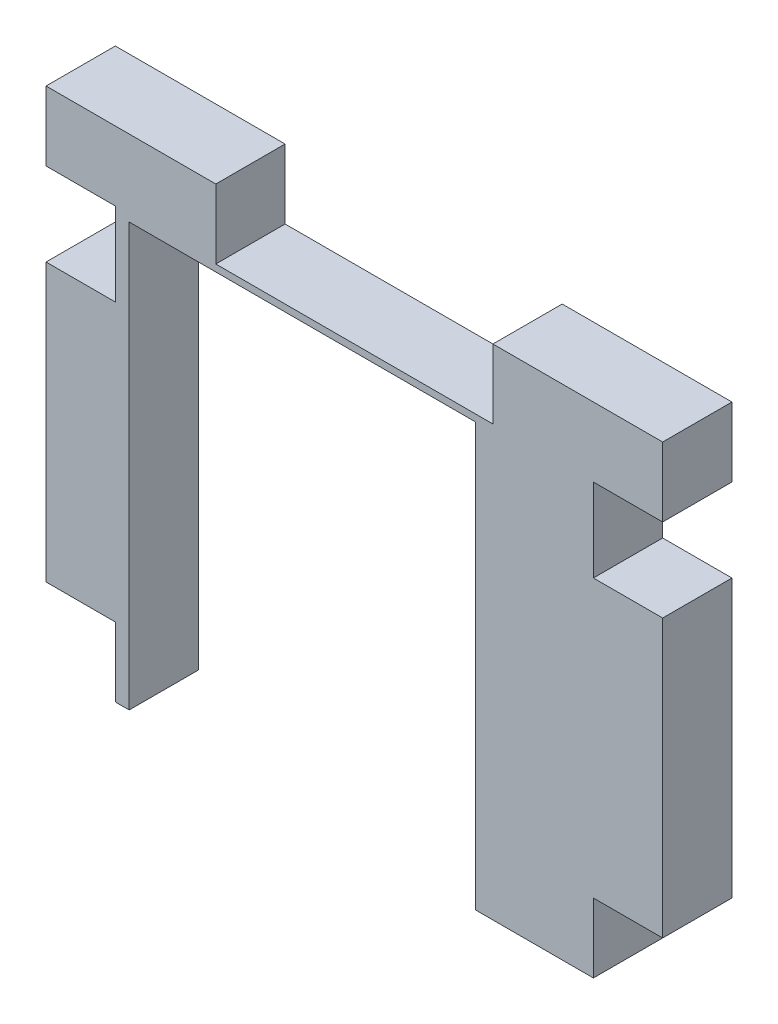
SolidWorks part; units mm, degrees
ref_plane "Front Plane" through (0, 0, 0) normal (0, 0, 1) x (1, 0, 0)
ref_plane "Top Plane" through (0, 0, 0) normal (0, 1, 0) x (1, 0, 0)
ref_plane "Right Plane" through (0, 0, 0) normal (1, 0, 0) x (0, 0, -1)
sketch "Sketch1" plane through (0, 0, 0) normal (0, 0, 1) x (1, 0, 0)
  line L0 (5, 36) -> (44.5, 36)
  line L1 (0, 0) -> (44.5, 0)
  line L2 (0, 0) -> (0, 41)
  line L3 (0, 41) -> (44.5, 41)
  line L4 (44.5, 0) -> (44.5, 41)
  line L5 (12.25, 0) -> (32.25, 0)
  line L6 (12.25, 0) -> (12.25, 5)
  line L7 (12.25, 5) -> (32.25, 5)
  line L8 (32.25, 0) -> (32.25, 5)
  line L9 (0, 10) -> (5, 10)
  line L10 (0, 10) -> (0, 30)
  line L11 (0, 30) -> (5, 30)
  line L12 (5, 10) -> (5, 30)
  line L13 (44.5, 30) -> (39.5, 30)
  line L14 (44.5, 30) -> (44.5, 10)
  line L15 (44.5, 10) -> (39.5, 10)
  line L16 (39.5, 30) -> (39.5, 10)
  line L17 (12.25, 41) -> (32.25, 41)
  line L18 (12.25, 41) -> (12.25, 36)
  line L19 (12.25, 36) -> (32.25, 36)
  line L20 (32.25, 41) -> (32.25, 36)
  line L21 (5, 36) -> (39.5, 36)
  line L22 (5, 36) -> (5, 5)
  line L23 (5, 5) -> (39.5, 5)
  line L24 (39.5, 36) -> (39.5, 5)
  line L25 (44.5, 36) -> (0, 36)
  line L26 (5, 10) -> (6, 10)
  line L27 (31, 35.5) -> (6, 35.5)
  line L28 (31, 35.5) -> (31, 3.5)
  line L29 (31, 3.5) -> (6, 3.5)
  line L30 (6, 35.5) -> (6, 3.5)
  dimension "D1" = 44.5
  dimension "D2" = 41
  dimension "D3" = 20
  dimension "D4" = 20
  dimension "D5" = 20
  dimension "D6" = 5
  dimension "D7" = 5
  dimension "D8" = 5
  dimension "D9" = 11
  dimension "D10" = 11
  dimension "D11" = 20
  dimension "D12" = 5
  dimension "D13" = 11
  dimension "D14" = 12.25
  dimension "D15" = 12.25
  dimension "D16" = 34.5
  dimension "D17" = 31
  dimension "D18" = 5
  dimension "D19" = 5
  dimension "D20" = 32
  dimension "D21" = 1
  dimension "D22" = 25
  dimension "D23" = 0.5
extrude "Boss-Extrude1" add sketch "Sketch1" along normal blind 5 contours L9 L12 L11 L2 | L13 L16 L15 L4 | L25 L0 L18 L3 L2 | L3 L20 L0 L4 | L30 L27 L28 L23 L24 L16 L0 L22 L12 | L30 L26 L22 L23 | L8 L7 L6 L5
